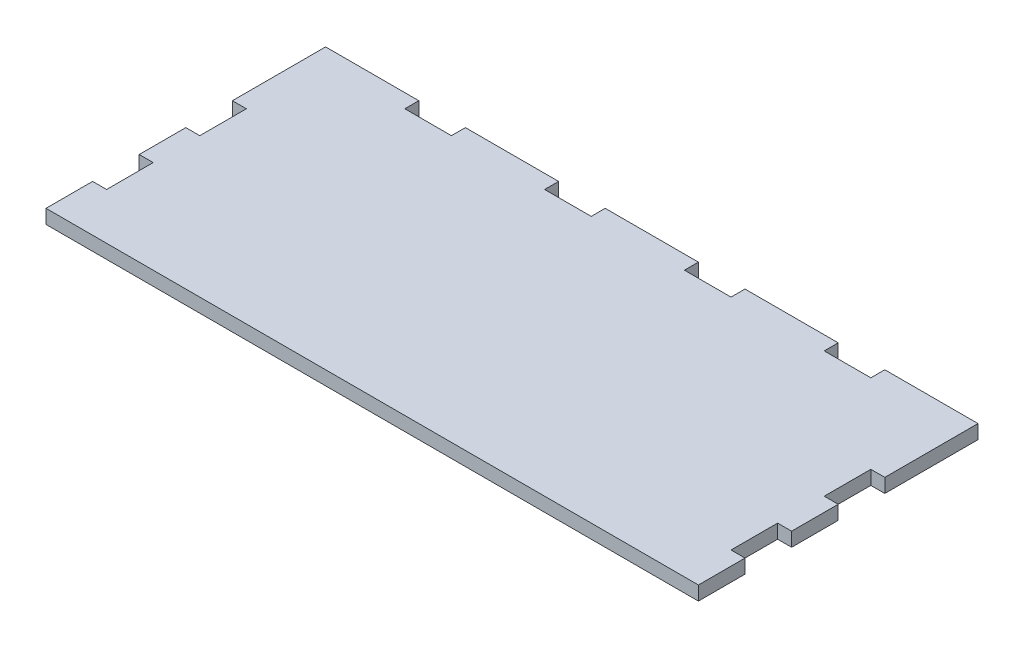
SolidWorks part; units mm, degrees
ref_plane "Front Plane" through (0, 0, 0) normal (0, 0, 1) x (1, 0, 0)
ref_plane "Top Plane" through (0, 0, 0) normal (0, 1, 0) x (1, 0, 0)
ref_plane "Right Plane" through (0, 0, 0) normal (1, 0, 0) x (0, 0, -1)
sketch "Sketch1" plane through (0, 0, 0) normal (0, 1, 0) x (1, 0, 0)
  line L1 (70, 30) -> (-70, 30)
  line L2 (70, 30) -> (70, -30)
  line L3 (70, -30) -> (-70, -30)
  line L4 (-70, 30) -> (-70, -30)
  line L5 (70, 30) -> (-70, -30) construction
  line L6 (70, -30) -> (-70, 30) construction
  point P0 (0, 0)
  dimension "D1" = 60
  dimension "D2" = 140
extrude "Boss-Extrude1" add sketch "Sketch1" along normal blind 3
sketch "Sketch2" plane through (0, 3, 0) normal (0, 1, 0) x (1, 0, 0)
  line L0 (70, -30) -> (70, 30) construction
  line L1 (70, -20) -> (67, -20)
  line L2 (70, -20) -> (70, -10)
  line L3 (70, -10) -> (67, -10)
  line L4 (67, -20) -> (67, -10)
  line L5 (-70, -30) -> (70, -30) construction
  line L6 (70, 0) -> (70, 10)
  line L7 (70, 0) -> (67, 0)
  line L8 (67, 0) -> (67, 10)
  line L9 (70, 10) -> (67, 10)
  line L10 (0, -30) -> (0, 30) construction
  line L11 (70, 30) -> (-70, 30) construction
  line L12 (-70, -10) -> (-67, -10)
  line L13 (-67, -20) -> (-67, -10)
  line L14 (-70, -20) -> (-67, -20)
  line L15 (-70, -20) -> (-70, -10)
  line L16 (-70, 0) -> (-67, 0)
  line L17 (-67, 0) -> (-67, 10)
  line L18 (-70, 10) -> (-67, 10)
  line L19 (-70, 0) -> (-70, 10)
  dimension "D1" = 3
  dimension "D2" = 10
  dimension "D3" = 10
  dimension "D4" = 2
extrude "Cut-Extrude1" cut sketch "Sketch2" against normal blind 10
sketch "Sketch3" plane through (0, 3, 0) normal (0, 1, 0) x (1, 0, 0)
  line L0 (70, 30) -> (-70, 30) construction
  line L1 (-50, 30) -> (-40, 30)
  line L2 (-50, 30) -> (-50, 27)
  line L3 (-50, 27) -> (-40, 27)
  line L4 (-40, 30) -> (-40, 27)
  line L5 (-70, 30) -> (-70, 10) construction
  line L6 (-20, 30) -> (-20, 27)
  line L7 (-20, 30) -> (-10, 30)
  line L8 (-10, 30) -> (-10, 27)
  line L9 (-20, 27) -> (-10, 27)
  line L10 (10, 30) -> (10, 27)
  line L11 (10, 30) -> (20, 30)
  line L12 (20, 30) -> (20, 27)
  line L13 (10, 27) -> (20, 27)
  line L14 (40, 30) -> (40, 27)
  line L15 (40, 30) -> (50, 30)
  line L16 (50, 30) -> (50, 27)
  line L17 (40, 27) -> (50, 27)
  point P8 (-40, 28.5)
  dimension "D1" = 20
  dimension "D2" = 10
  dimension "D4" = 3
  dimension "D3" = 4
extrude "Cut-Extrude2" cut sketch "Sketch3" against normal blind 13
